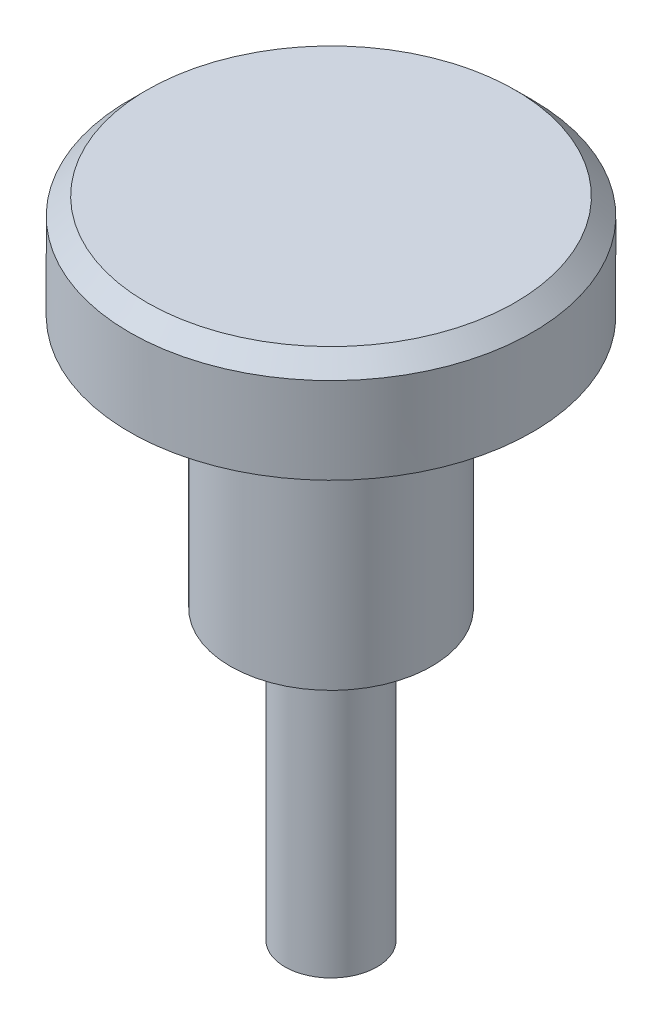
SolidWorks part; units mm, degrees
ref_plane "Front Plane" through (0, 0, 0) normal (0, 0, 1) x (1, 0, 0)
ref_plane "Top Plane" through (0, 0, 0) normal (0, 1, 0) x (1, 0, 0)
ref_plane "Right Plane" through (0, 0, 0) normal (1, 0, 0) x (0, 0, -1)
sketch "Sketch3" plane through (0, 0, 0) normal (0, 0, 1) x (1, 0, 0)
  line L0 (0, 0) -> (0, 112)
  line L1 (0, 0) -> (8, 0)
  line L2 (8, 0) -> (8, 50)
  line L3 (8, 50) -> (17.5, 50)
  line L4 (17.5, 50) -> (17.5, 94)
  line L5 (0, 112) -> (35, 112)
  line L6 (35, 112) -> (35, 94)
  line L7 (35, 94) -> (17.5, 94)
  dimension "D1" = 112
  dimension "D2" = 8
  dimension "D3" = 50
  dimension "D4" = 9.5
  dimension "D5" = 44
  dimension "D6" = 35
revolve "Revolve1" add sketch "Sketch3" angle 360 about L0
cosmetic thread "Cosmetic Thread1" parameters "D2"=13.797
cosmetic thread "Cosmetic Thread2" parameters "D1"=25, "D2"=13.797
cosmetic thread "Cosmetic Thread3" parameters "D1"=25, "D2"=13.797
chamfer "Chamfer1" distance 3 angle 45 1 edges at (0, 112, -35)
